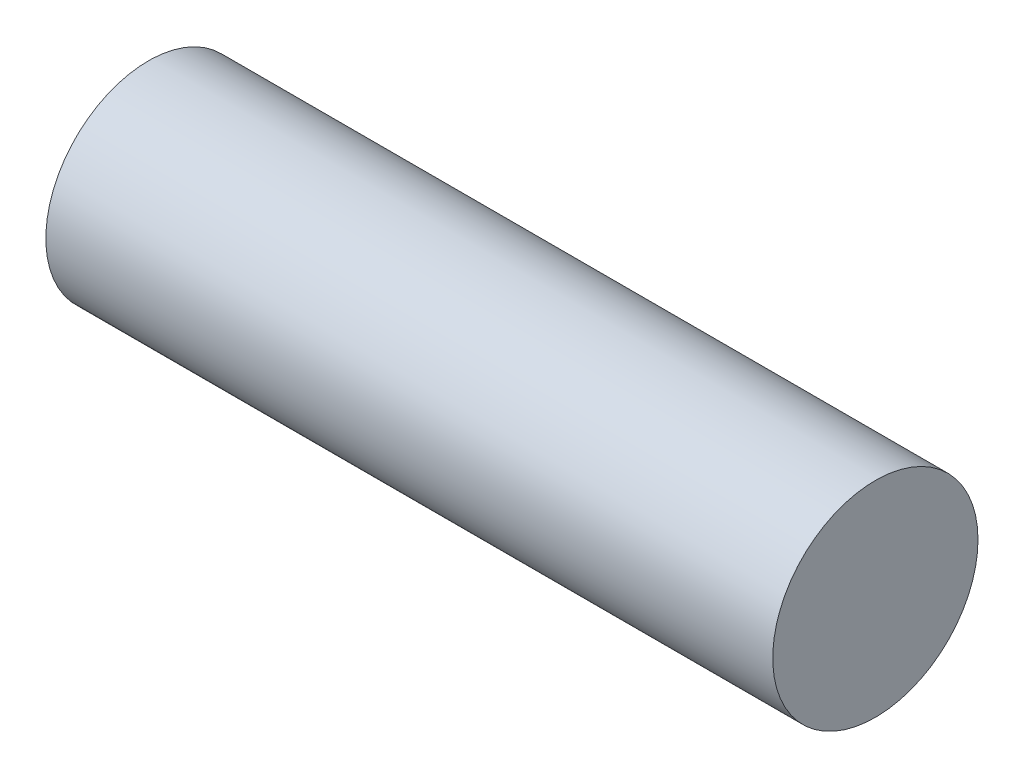
SolidWorks part; units mm, degrees
ref_plane "Front Plane" through (0, 0, 0) normal (0, 0, 1) x (1, 0, 0)
ref_plane "Top Plane" through (0, 0, 0) normal (0, 1, 0) x (1, 0, 0)
ref_plane "Right Plane" through (0, 0, 0) normal (1, 0, 0) x (0, 0, -1)
sketch "Sketch1" plane through (0, 0, 0) normal (1, 0, 0) x (0, 0, -1)
  circle A0 centre (0, 0) radius 4.4831
  dimension "D1" = 8.9662
extrude "Boss-Extrude1" add sketch "Sketch1" along normal blind 31.75 contours A0
